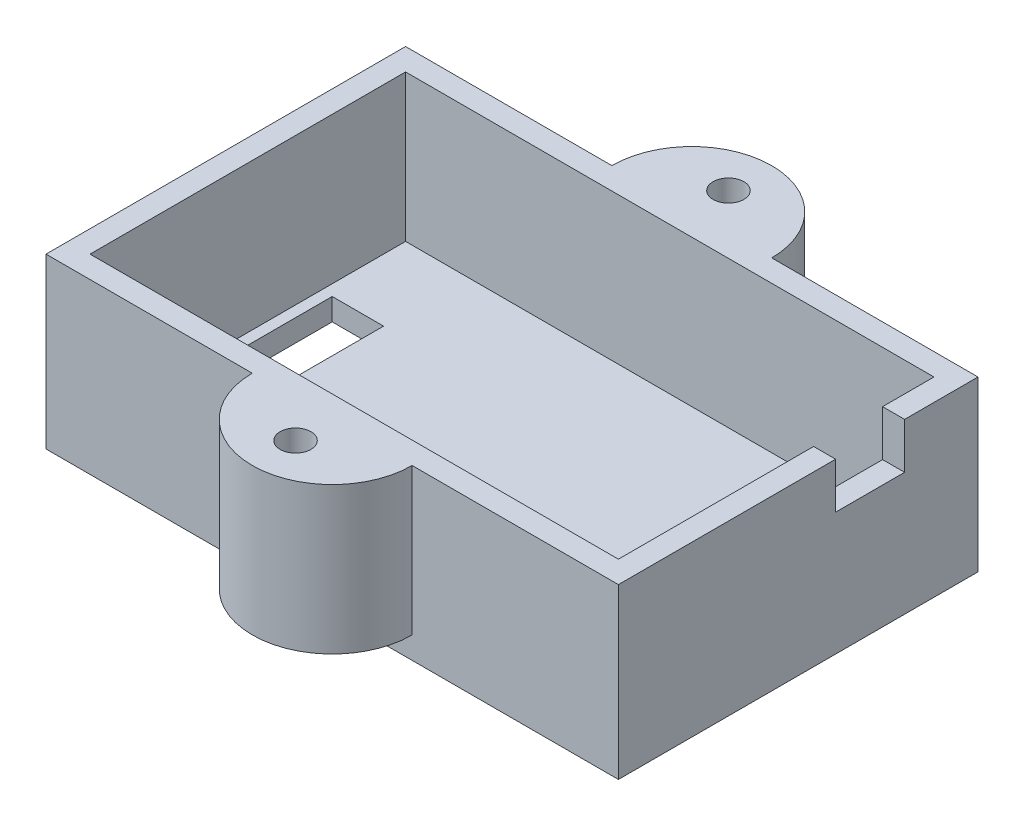
SolidWorks part; units mm, degrees
ref_plane "Front Plane" through (0, 0, 0) normal (0, 0, 1) x (1, 0, 0)
ref_plane "Top Plane" through (0, 0, 0) normal (0, 1, 0) x (1, 0, 0)
ref_plane "Right Plane" through (0, 0, 0) normal (1, 0, 0) x (0, 0, -1)
sketch "Sketch1" plane through (0, 0, 0) normal (0, 1, 0) x (1, 0, 0)
  line L0 (-39, 24.5) -> (-39, 10.8861)
  line L1 (-36, 21.5) -> (36, 21.5)
  line L2 (-36, 21.5) -> (-36, -21.5)
  line L3 (-36, -21.5) -> (36, -21.5)
  line L4 (36, 21.5) -> (36, -21.5)
  line L5 (-36, 21.5) -> (36, -21.5) construction
  line L6 (-36, -21.5) -> (36, 21.5) construction
  line L7 (-39, -24.5) -> (-10.89, -24.5)
  line L8 (39, 24.5) -> (39, 10.8861)
  line L9 (-39, 24.5) -> (-10.89, 24.5)
  line L10 (39, -10.8861) -> (39, 10.8861)
  line L11 (-39, -10.8861) -> (-39, -24.5)
  line L12 (-39, 24.5) -> (-39, -24.5) construction
  line L13 (0, -24.5) -> (0, 24.5) construction
  line L14 (39, -10.8861) -> (39, -24.5)
  line L15 (39, 24.5) -> (39, -24.5) construction
  line L16 (-39, -10.8861) -> (-39, 10.8861)
  line L17 (10.89, -24.5) -> (39, -24.5)
  line L18 (-39, -24.5) -> (39, -24.5) construction
  line L19 (10.89, 24.5) -> (39, 24.5)
  line L20 (-39, 24.5) -> (39, 24.5) construction
  arc A4 (10.89, -24.5) -> (-10.89, -24.5) centre (0, -24.5) cw
  circle A5 centre (0, -29.5) radius 2.1
  arc A6 (10.89, 24.5) -> (-10.89, 24.5) centre (0, 24.5) ccw
  circle A7 centre (0, 29.5) radius 2.1
  point P0 (0, 0)
  dimension "D4" = 10.89
  dimension "D6" = 10.89
  dimension "D7" = 4.2
  dimension "D5" = 4.2
  dimension "D1" = 43
  dimension "D2" = 72
  dimension "D8" = 5
  dimension "D9" = 5
  dimension "D3" = 3
extrude "Boss-Extrude1" add sketch "Sketch1" along normal blind 20
sketch "Sketch2" plane through (0, 0, 0) normal (0, -1, 0) x (1, 0, 0)
  line L1 (39, 24.5) -> (-39, 24.5)
  line L2 (39, 24.5) -> (39, -24.5)
  line L3 (39, -24.5) -> (-39, -24.5)
  line L4 (-39, 24.5) -> (-39, -24.5)
extrude "Boss-Extrude2" add sketch "Sketch2" along normal blind 3
sketch "Sketch3" plane through (0, 0, 0) normal (0, 1, 0) x (1, 0, 0)
  line L0 (-36, 21.5) -> (-36, -21.5) construction
  line L1 (-27.5, -10) -> (-34.5, -10)
  line L2 (-27.5, -10) -> (-27.5, 10)
  line L3 (-27.5, 10) -> (-34.5, 10)
  line L4 (-34.5, -10) -> (-34.5, 10)
  line L5 (-27.5, -10) -> (-34.5, 10) construction
  line L6 (-27.5, 10) -> (-34.5, -10) construction
  line L7 (-36, -21.5) -> (36, -21.5) construction
  point P0 (-31, 0)
  dimension "D1" = 5
  dimension "D2" = 21.5
  dimension "D3" = 7
  dimension "D4" = 20
extrude "Cut-Extrude1" cut sketch "Sketch3" against normal blind 10
sketch "Sketch4" plane through (39, 0, 0) normal (1, 0, 0) x (0, 0, -1)
  line L0 (-24.5, 20) -> (24.5, 20) construction
  line L1 (5.1, 20) -> (14.5, 20)
  line L2 (5.1, 20) -> (5.1, 13.75)
  line L3 (5.1, 13.75) -> (14.5, 13.75)
  line L4 (14.5, 20) -> (14.5, 13.75)
  line L5 (24.5, 20) -> (24.5, -3) construction
  dimension "D1" = 9.4
  dimension "D2" = 6.25
  dimension "D3" = 10
extrude "Cut-Extrude2" cut sketch "Sketch4" against normal blind 10
